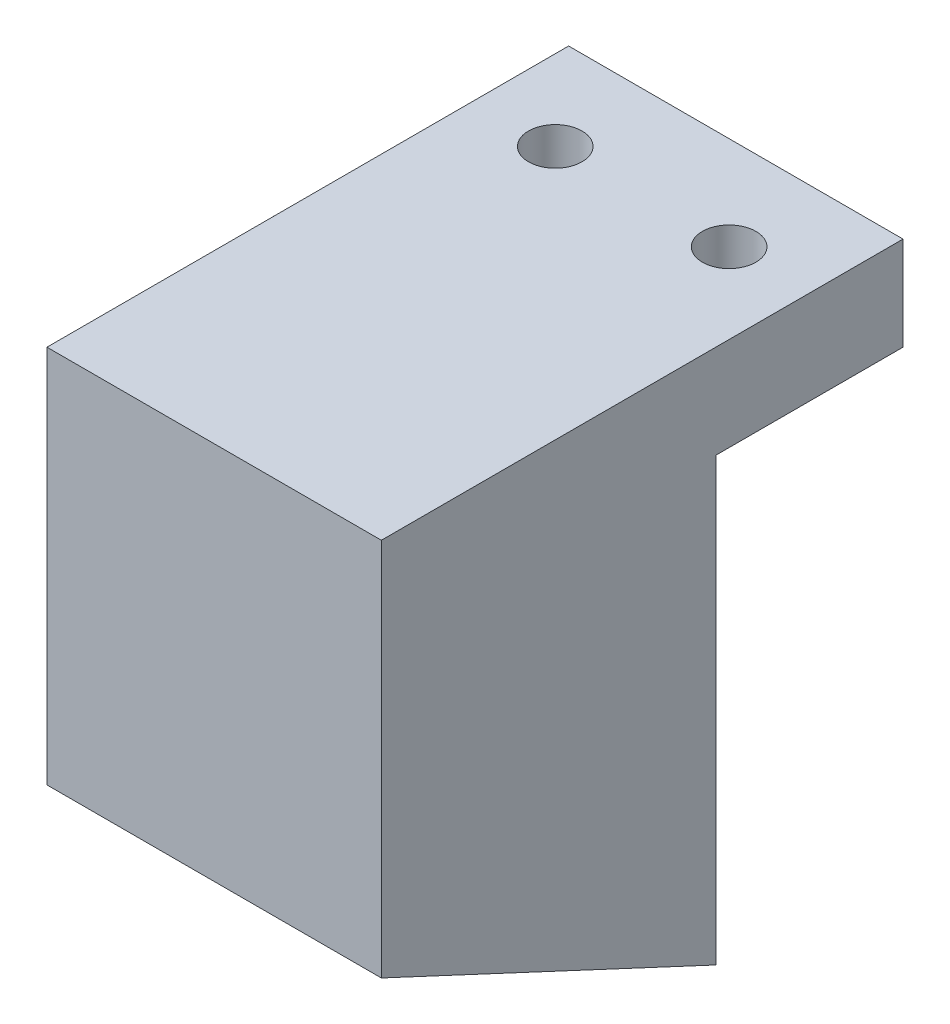
SolidWorks part; units mm, degrees
material "ABS"
ref_plane "Front Plane" through (0, 0, 0) normal (0, 0, 1) x (1, 0, 0)
ref_plane "Top Plane" through (0, 0, 0) normal (0, 1, 0) x (1, 0, 0)
ref_plane "Right Plane" through (0, 0, 0) normal (1, 0, 0) x (0, 0, -1)
sketch "Sketch1" plane through (0, 0, 0) normal (0, 1, 0) x (1, 0, 0)
  line L1 (-76.9048, 16.0714) -> (-51.9048, 16.0714)
  line L2 (-76.9048, 16.0714) -> (-76.9048, -8.9286)
  line L3 (-76.9048, -8.9286) -> (-51.9048, -8.9286)
  line L4 (-51.9048, 16.0714) -> (-51.9048, -8.9286)
  dimension "D1" = 25
  dimension "D2" = 25
extrude "Boss-Extrude1" add sketch "Sketch1" along normal blind 40
sketch "Sketch2" plane through (-51.9048, 0, 0) normal (1, 0, 0) x (0, 0, -1)
  line L3 (-8.9286, 0) -> (16.0714, 0) construction
  line L5 (16.0714, 0) -> (-8.9286, 0)
  line L6 (16.0714, 40) -> (16.0714, 0) construction
  line L7 (-8.9286, 40) -> (-8.9286, 0) construction
  line L8 (-8.9286, 0) -> (-8.9286, 11.6577)
  line L9 (-8.9286, 11.6577) -> (16.0714, 0)
  dimension "D1" = 25
  dimension "D2" = 0
extrude "Cut-Extrude1" cut sketch "Sketch2" against normal blind 40
sketch "Sketch3" plane through (0, 6.1557, -2.8705) normal (0, -0.9063, 0.4226) x (1, 0, 0)
  line L0 (-76.9048, 13.0188) -> (-51.9048, 13.0188) construction
  line L1 (-51.9048, -14.5657) -> (-51.9048, 13.0188) construction
  circle A0 centre (-64.4048, -0.7712) radius 1.5
  point P4 (-64.4048, 13.0188)
  dimension "D1" = 13.79
  dimension "D2" = 12.5
  dimension "D3" = 3
extrude "Cut-Extrude2" cut sketch "Sketch3" against normal blind 36
sketch "Sketch4" plane through (0, 0, -16.0714) normal (0, 0, -1) x (-1, 0, 0)
  line L0 (51.9048, 40) -> (51.9048, 0) construction
  line L1 (76.9048, 40) -> (51.9048, 40)
  line L2 (76.9048, 40) -> (76.9048, 33)
  line L3 (76.9048, 33) -> (51.9048, 33)
  line L4 (51.9048, 40) -> (51.9048, 33)
  dimension "D1" = 7
extrude "Boss-Extrude2" add sketch "Sketch4" along normal blind 14
sketch "Sketch5" plane through (0, 33, 0) normal (0, -1, 0) x (-1, 0, 0)
  line L0 (51.9048, 30.0714) -> (76.9048, 30.0714) construction
  line L1 (51.9048, 30.0714) -> (51.9048, 16.0714) construction
  line L2 (76.9048, 30.0714) -> (76.9048, 16.0714) construction
  circle A0 centre (70.9048, 23.0714) radius 2
  circle A1 centre (57.9048, 23.0714) radius 2
  dimension "D1" = 4
  dimension "D2" = 4
  dimension "D3" = 7
  dimension "D4" = 6
  dimension "D5" = 6
  dimension "D6" = 7
extrude "Cut-Extrude3" cut sketch "Sketch5" against normal blind 14
